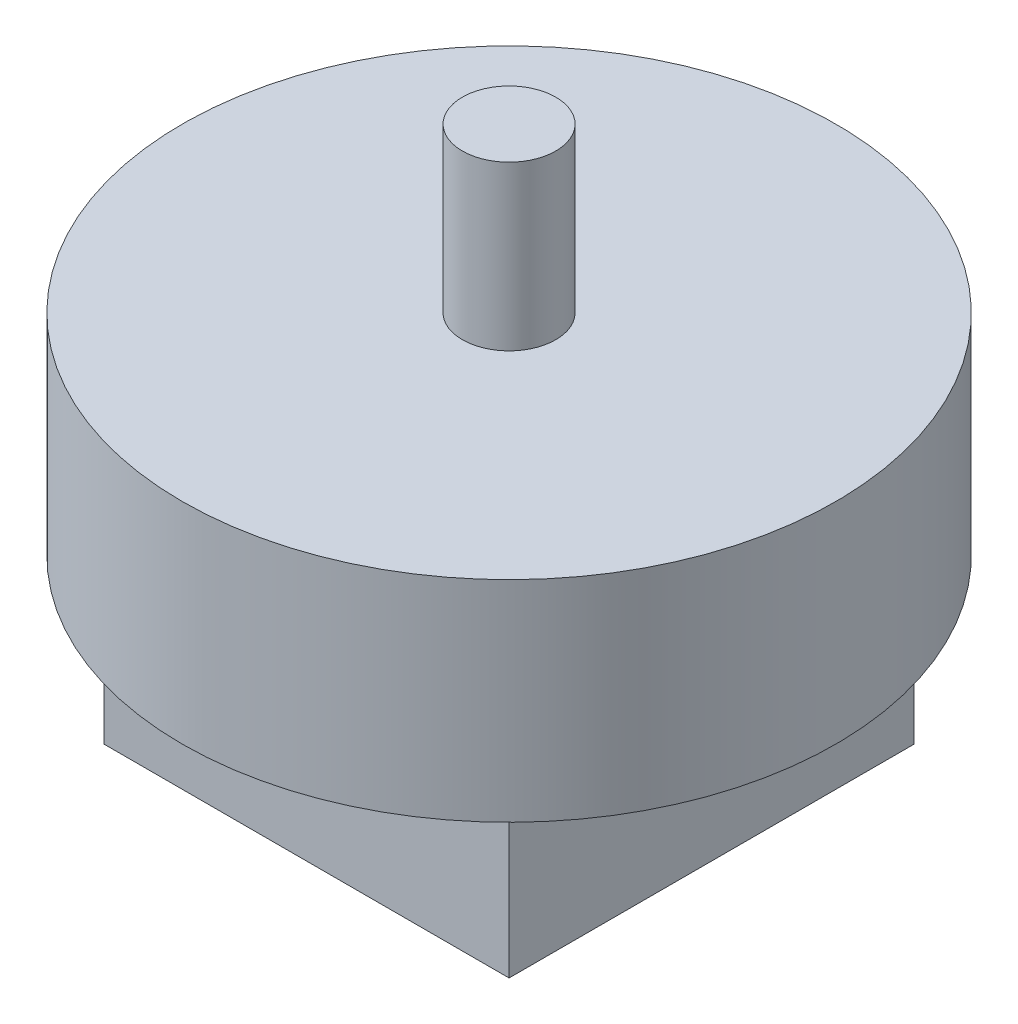
SolidWorks part; units mm, degrees
ref_plane "Front Plane" through (0, 0, 0) normal (0, 0, 1) x (1, 0, 0)
ref_plane "Top Plane" through (0, 0, 0) normal (0, 1, 0) x (1, 0, 0)
ref_plane "Right Plane" through (0, 0, 0) normal (1, 0, 0) x (0, 0, -1)
sketch "Sketch1" plane through (0, 0, 0) normal (0, 1, 0) x (1, 0, 0)
  circle A0 centre (0, 0) radius 14
  dimension "D1" = 28
extrude "Boss-Extrude1" add sketch "Sketch1" along normal blind 9
sketch "Sketch3" plane through (0, 0, 0) normal (0, -1, 0) x (1, 0, 0)
  line L1 (-8.675, 8.675) -> (8.675, 8.675)
  line L2 (-8.675, 8.675) -> (-8.675, -8.675)
  line L3 (-8.675, -8.675) -> (8.675, -8.675)
  line L4 (8.675, 8.675) -> (8.675, -8.675)
  line L5 (-8.675, 8.675) -> (8.675, -8.675) construction
  line L6 (-8.675, -8.675) -> (8.675, 8.675) construction
  point P1 (0, 0)
  dimension "D1" = 17.35
  dimension "D2" = 17.35
extrude "Boss-Extrude2" add sketch "Sketch3" along normal blind 7
sketch "Sketch4" plane through (0, -7, 0) normal (0, -1, 0) x (1, 0, 0)
  line L0 (8.675, 8.675) -> (-8.675, 8.675) construction
  line L1 (8.675, -8.675) -> (8.675, 8.675) construction
  circle A0 centre (-5.952, 5.675) radius 1.7
  circle A1 centre (-5.952, -5.3164) radius 1.7
  circle A2 centre (5.675, -5.3164) radius 1.7
  circle A3 centre (5.675, 5.675) radius 1.7
  point P8 (0, 0)
  point P9 (0, 0)
  point P10 (0, 0)
  point P11 (0, 0)
  point P12 (0, 0)
  dimension "D1" = 3.4
  dimension "D2" = 16
  dimension "D3" = 16
  dimension "D4" = 8.2239
  dimension "D5" = 3
  dimension "D6" = 3
extrude "Cut-Extrude1" cut sketch "Sketch4" against normal blind 7
sketch "Sketch5" plane through (0, 9, 0) normal (0, 1, 0) x (1, 0, 0)
  circle A0 centre (0, 0) radius 2
  dimension "D1" = 4
extrude "Boss-Extrude3" add sketch "Sketch5" along normal blind 7
